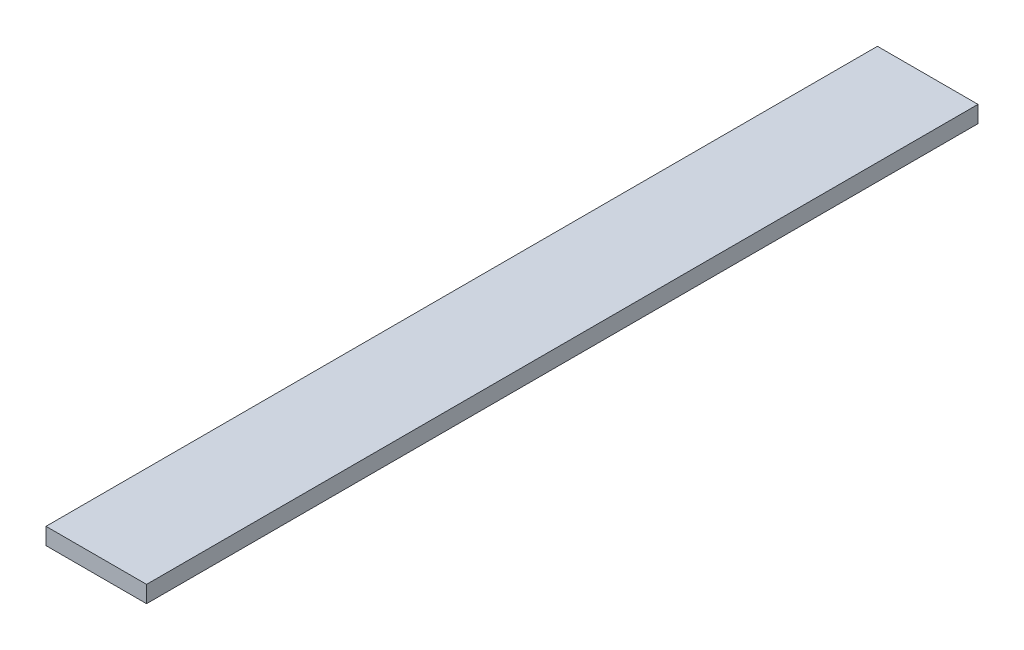
SolidWorks part; units mm, degrees
ref_plane "Front Plane" through (0, 0, 0) normal (0, 0, 1) x (1, 0, 0)
ref_plane "Top Plane" through (0, 0, 0) normal (0, 1, 0) x (1, 0, 0)
ref_plane "Right Plane" through (0, 0, 0) normal (1, 0, 0) x (0, 0, -1)
sketch "Sketch1" plane through (0, 0, 0) normal (0, 0, 1) x (1, 0, 0)
  line L1 (38.1, -6.35) -> (-38.1, -6.35)
  line L2 (38.1, -6.35) -> (38.1, 6.35)
  line L3 (38.1, 6.35) -> (-38.1, 6.35)
  line L4 (-38.1, -6.35) -> (-38.1, 6.35)
  line L5 (0, 6.35) -> (0, -6.35) construction
  line L6 (38.1, 0) -> (-38.1, 0) construction
  point P0 (0, 0)
  dimension "D1" = 12.7
  dimension "D2" = 76.2
extrude "Boss-Extrude1" add sketch "Sketch1" along normal blind 630
